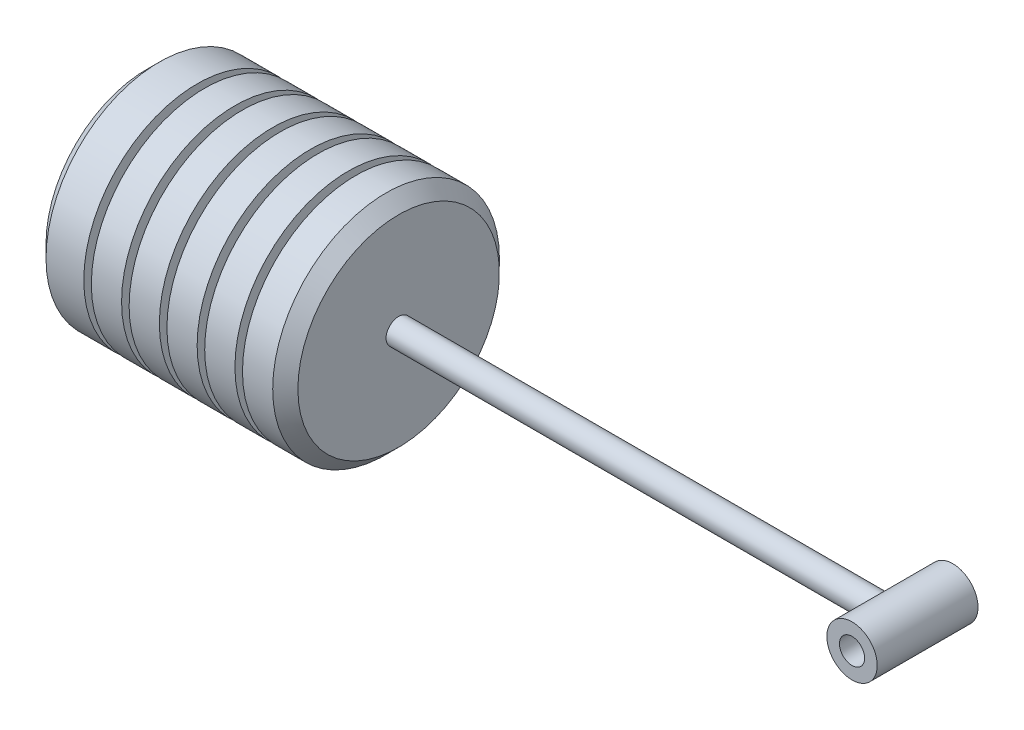
SolidWorks part; units mm, degrees
material "Латунь"
ref_plane "Спереди" through (0, 0, 0) normal (0, 0, 1) x (1, 0, 0)
ref_plane "Сверху" through (0, 0, 0) normal (0, 1, 0) x (1, 0, 0)
ref_plane "Справа" through (0, 0, 0) normal (1, 0, 0) x (0, 0, -1)
sketch "Эскиз1" plane through (0, 0, 0) normal (0, 0, 1) x (1, 0, 0)
  line L0 (-82.8621, 0) -> (269.069, 0) construction
  line L1 (0, 150.5172) -> (0, -188.3793) construction
  line L2 (0, 40) -> (5, 45)
  line L3 (0, 0) -> (100, 0)
  line L4 (0, 0) -> (0, 40)
  line L5 (5, 45) -> (20, 45)
  line L6 (100, 0) -> (100, 40)
  line L7 (20, 45) -> (20, 40)
  line L8 (20, 40) -> (23, 40)
  line L9 (23, 40) -> (23, 45)
  line L10 (23, 45) -> (35, 45)
  line L11 (35, 45) -> (35, 40)
  line L12 (38, 40) -> (38, 45)
  line L13 (35, 40) -> (38, 40)
  line L14 (50, 45) -> (50, 40)
  line L15 (53, 40) -> (53, 45)
  line L16 (50, 40) -> (53, 40)
  line L17 (65, 45) -> (65, 40)
  line L18 (68, 40) -> (68, 45)
  line L19 (65, 40) -> (68, 40)
  line L20 (80, 45) -> (80, 40)
  line L21 (83, 40) -> (83, 45)
  line L22 (80, 40) -> (83, 40)
  line L23 (38, 45) -> (50, 45)
  line L24 (53, 45) -> (65, 45)
  line L25 (68, 45) -> (80, 45)
  line L26 (83, 45) -> (95, 45)
  line L27 (95, 45) -> (100, 40)
  point P6 (100, 45)
  point P7 (0, 45)
  dimension "D1" = 45
  dimension "D2" = 100
  dimension "D3" = 20
  dimension "D4" = 3
  dimension "D6" = 5
  dimension "D8" = 15
  dimension "D7" = 5
revolve "Повернуть1" add sketch "Эскиз1" angle 360 about L0
sketch "Эскиз2" plane through (100, 0, 0) normal (1, 0, 0) x (0, 0, -1)
  line L0 (-62.457, 0) -> (55.6601, 0) construction
  circle A0 centre (0, 0) radius 5
  dimension "D1" = 10
extrude "Бобышка-Вытянуть1" add sketch "Эскиз2" along normal blind 200
sketch "Эскиз3" plane through (0, 0, 0) normal (0, 0, 1) x (1, 0, 0)
  line L0 (-27.3751, 0) -> (539.4735, 0) construction
  line L1 (300, -5) -> (300, 5) construction
  circle A0 centre (300, 0) radius 10
  dimension "D1" = 20
extrude "Бобышка-Вытянуть2" add sketch "Эскиз3" along normal mid plane 40
sketch "Эскиз4" plane through (0, 0, 20) normal (0, 0, 1) x (1, 0, 0)
  line L0 (0, 78.3142) -> (0, -64.0086) construction
  circle A0 centre (300, 0) radius 5
  dimension "D1" = 10
extrude "Вырез-Вытянуть1" cut sketch "Эскиз4" against normal up to surface (40 mm away) up to face at (310, 0, -20)
